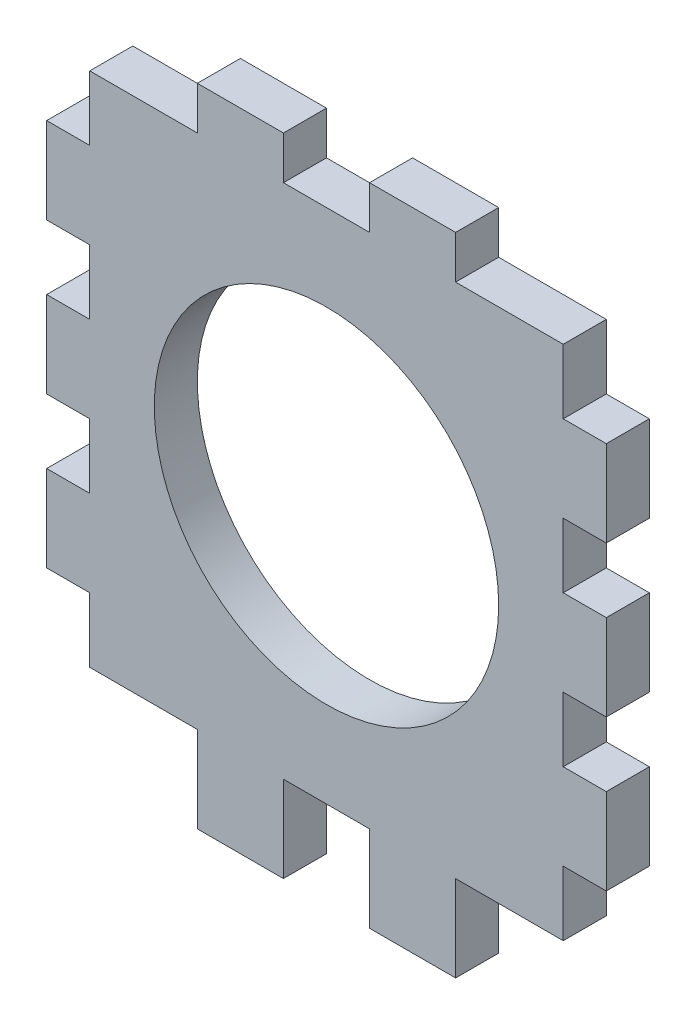
SolidWorks part; units mm, degrees
material "Beech"
ref_plane "Front" through (0, 0, 0) normal (0, 0, 1) x (1, 0, 0)
ref_plane "Top" through (0, 0, 0) normal (0, 1, 0) x (1, 0, 0)
ref_plane "Right" through (0, 0, 0) normal (1, 0, 0) x (0, 0, -1)
sketch "Sketch1" plane through (0, 0, 0) normal (0, 0, 1) x (1, 0, 0)
  line L0 (-7.5, -15) -> (-7.5, -20)
  line L1 (-13.75, -15) -> (13.75, -15)
  line L2 (-13.75, -15) -> (-13.75, 15) construction
  line L3 (-13.75, 15) -> (13.75, 15)
  line L4 (13.75, -15) -> (13.75, 15) construction
  line L5 (-13.75, -15) -> (13.75, 15) construction
  line L6 (-13.75, 15) -> (13.75, -15) construction
  line L7 (2.5, 15) -> (7.5, 15)
  line L8 (2.5, 15) -> (2.5, 17.5)
  line L9 (2.5, 17.5) -> (7.5, 17.5)
  line L10 (7.5, 15) -> (7.5, 17.5)
  line L11 (2.5, 15) -> (7.5, 17.5) construction
  line L12 (2.5, 17.5) -> (7.5, 15) construction
  line L13 (2.5, -15) -> (7.5, -15)
  line L14 (2.5, -15) -> (2.5, -20)
  line L15 (2.5, -20) -> (7.5, -20)
  line L16 (7.5, -15) -> (7.5, -20)
  line L17 (2.5, -15) -> (7.5, -20) construction
  line L18 (2.5, -20) -> (7.5, -15) construction
  line L19 (-7.5, -15) -> (-2.5, -15)
  line L20 (-2.5, -15) -> (-2.5, -20)
  line L21 (-7.5, -20) -> (-2.5, -20)
  line L30 (-7.5, 15) -> (-7.5, 17.5)
  line L31 (-7.5, 15) -> (-2.5, 15)
  line L32 (-2.5, 15) -> (-2.5, 17.5)
  line L33 (-7.5, 17.5) -> (-2.5, 17.5)
  line L42 (-27.5, 15) -> (-27.5, 17.5) [skipped]
  line L43 (-27.5, 17.5) -> (-22.5, 17.5) [skipped]
  line L44 (-22.5, 15) -> (-22.5, 17.5) [skipped]
  line L45 (-27.5, 15) -> (-22.5, 15) [skipped]
  line L46 (-17.5, 15) -> (-17.5, 17.5) [skipped]
  line L47 (-17.5, 17.5) -> (-12.5, 17.5) [skipped]
  line L48 (-12.5, 15) -> (-12.5, 17.5) [skipped]
  line L49 (-17.5, 15) -> (-12.5, 15) [skipped]
  line L50 (-27.5, -15) -> (-27.5, -20) [skipped]
  line L51 (-27.5, -20) -> (-22.5, -20) [skipped]
  line L52 (-22.5, -15) -> (-22.5, -20) [skipped]
  line L53 (-27.5, -15) -> (-22.5, -15) [skipped]
  line L54 (-17.5, -15) -> (-17.5, -20) [skipped]
  line L55 (-17.5, -20) -> (-12.5, -20) [skipped]
  line L56 (-12.5, -15) -> (-12.5, -20) [skipped]
  line L57 (-17.5, -15) -> (-12.5, -15) [skipped]
  line L58 (0, 5.4028) -> (0, -4.5111) construction
  line L59 (-13.75, 15) -> (-13.75, 11.25)
  line L60 (-13.75, 11.25) -> (-16.25, 11.25)
  line L61 (-16.25, 11.25) -> (-16.25, 6.25)
  line L62 (-16.25, 6.25) -> (-13.75, 6.25)
  line L63 (-13.75, 6.25) -> (-13.75, 2.5)
  line L64 (-13.75, 2.5) -> (-16.25, 2.5)
  line L65 (-16.25, 2.5) -> (-16.25, -2.5)
  line L66 (-16.25, -2.5) -> (-13.75, -2.5)
  line L67 (-13.75, -2.5) -> (-13.75, -6.25)
  line L68 (-13.75, -6.25) -> (-16.25, -6.25)
  line L69 (-16.25, -6.25) -> (-16.25, -11.25)
  line L70 (-16.25, -11.25) -> (-13.75, -11.25)
  line L71 (-13.75, -11.25) -> (-13.75, -15)
  line L72 (13.75, -11.25) -> (13.75, -15)
  line L73 (16.25, -11.25) -> (13.75, -11.25)
  line L74 (16.25, -6.25) -> (16.25, -11.25)
  line L75 (13.75, -6.25) -> (16.25, -6.25)
  line L76 (13.75, -2.5) -> (13.75, -6.25)
  line L77 (16.25, -2.5) -> (13.75, -2.5)
  line L78 (16.25, 2.5) -> (16.25, -2.5)
  line L79 (13.75, 2.5) -> (16.25, 2.5)
  line L80 (13.75, 6.25) -> (13.75, 2.5)
  line L81 (16.25, 6.25) -> (13.75, 6.25)
  line L82 (16.25, 11.25) -> (16.25, 6.25)
  line L83 (13.75, 11.25) -> (16.25, 11.25)
  line L84 (13.75, 15) -> (13.75, 11.25)
  circle A0 centre (0, 0) radius 10
  point P0 (0, 0)
  point P10 (5, 16.25)
  point P16 (5, -17.5)
  dimension "D15" = 20
  dimension "D1" = 30
  dimension "D2" = 27.5
  dimension "D3" = 6.25
  dimension "D4" = 5
  dimension "D5" = 5
  dimension "D6" = 6.25
  dimension "D7" = 5
  dimension "D8" = 2.5
  dimension "D11" = 5
  dimension "D12" = 5
  dimension "D13" = 2.5
  dimension "D14" = 5
  dimension "D9" = 4
  dimension "D10" = 4
  dimension "D16" = 3
extrude "Boss-Extrude1" add sketch "Sketch1" along normal blind 2.5
